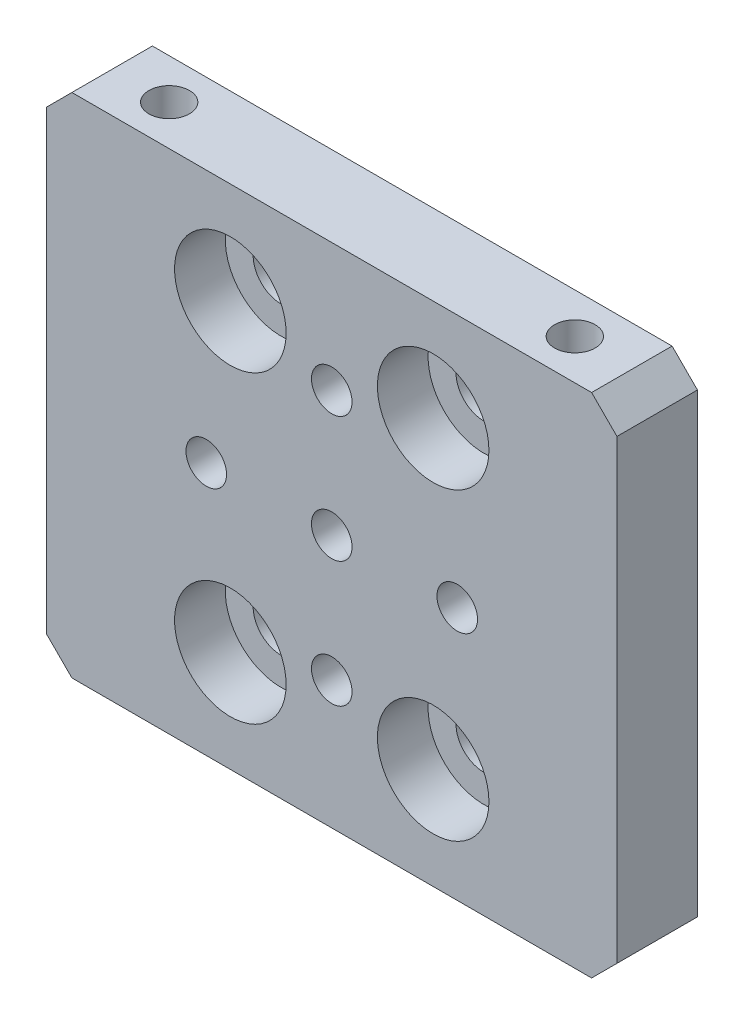
SolidWorks part; units mm, degrees
ref_plane "Front Plane" through (0, 0, 0) normal (0, 0, 1) x (1, 0, 0)
ref_plane "Top Plane" through (0, 0, 0) normal (0, 1, 0) x (1, 0, 0)
ref_plane "Right Plane" through (0, 0, 0) normal (1, 0, 0) x (0, 0, -1)
sketch "Sketch1" plane through (0, 0, 0) normal (0, 0, 1) x (1, 0, 0)
  line L1 (-11.25, 10) -> (11.25, 10)
  line L2 (-11.25, 10) -> (-11.25, -10)
  line L3 (-11.25, -10) -> (11.25, -10)
  line L4 (11.25, 10) -> (11.25, -10)
  line L5 (0, -10) -> (0, 10) construction
  line L6 (-11.25, 0) -> (11.25, 0) construction
  point P0 (0, 0)
  dimension "D1" = 20
  dimension "D2" = 22.5
extrude "Boss-Extrude1" add sketch "Sketch1" along normal blind 3.175
hole_wizard "CBORE for M2 SHCS1" positions "Sketch2" profile "Sketch3" counterbore size "M2" standard "ANSI Metric" end condition through all
sketch "Sketch2" plane through (0, 0, 3.175) normal (0, 0, 1) x (1, 0, 0)
  line L1 (-4, -6) -> (4, -6)
  line L2 (-4, -6) -> (-4, 6)
  line L3 (-4, 6) -> (4, 6)
  line L4 (4, -6) -> (4, 6)
  line L5 (0, 6) -> (0, -6) construction
  line L6 (-4, 0) -> (4, 0) construction
  point P2 (4, 6)
  point P909 (-4, -6)
  point P910 (-4, 6)
  point P924 (4, -6)
  dimension "D1" = 8
  dimension "D2" = 12
sketch "Sketch3" plane through (4, 6, 3.175) normal (1, 0, 0) x (0, -1, 0)
  line L0 (0, 0) -> (0, 3.175)
  line L1 (0, 3.175) -> (1.1, 3.175)
  line L3 (1.1, 3.175) -> (1.1, 2)
  line L4 (1.1, 2) -> (2.2, 2)
  line L5 (2.2, 2) -> (2.2, 0)
  line L7 (2.2, 0) -> (0, 0)
  line L11 (0, -6.35) -> (0, 107.95) construction
  dimension "Thru Hole Dia." = 2.2
  dimension "Thru Hole Depth" = 3.175
  dimension "C'Bore Dia." = 4.4
  dimension "C'Bore Depth" = 2
hole_wizard "Tap Drill for M2x0.4 Tap1" positions "Sketch5" profile "Sketch6" hole size "M2x0.4" standard "ANSI Metric" end condition through all
sketch "Sketch5" plane through (0, 10, 0) normal (0, 1, 0) x (1, 0, 0)
  line L0 (0, 0) -> (0, -3.175) construction
  line L1 (11.25, -3.175) -> (-11.25, -3.175) construction
  line L3 (0, -1.5875) -> (-8, -1.5875) construction
  point P9 (-8, -1.5875)
  point P16 (8, -1.5875)
  dimension "D1" = 8
sketch "Sketch6" plane through (8, 10, 1.5875) normal (1, 0, 0) x (0, 0, 1)
  line L0 (0, 0) -> (0, 20)
  line L1 (0, 20) -> (0.8, 20)
  line L2 (0.8, 20) -> (0.8, 0)
  line L5 (0.8, 0) -> (0, 0)
  line L11 (0, -6.35) -> (0, 107.95) construction
  dimension "Thru Hole Dia." = 1.6
  dimension "Thru Hole Depth" = 20
hole_wizard "Tap Drill for M2x0.4 Tap2" positions "Sketch7" profile "Sketch8" hole size "M2x0.4" standard "ANSI Metric" end condition through all
sketch "Sketch7" plane through (0, 0, 3.175) normal (0, 0, 1) x (1, 0, 0)
  line L2 (-4.9497, 0) -> (0, -4.9497)
  line L3 (-4.9497, 0) -> (0, 4.9497)
  line L4 (0, -4.9497) -> (4.9497, 0)
  line L5 (0, 4.9497) -> (4.9497, 0)
  line L6 (2.4749, -2.4749) -> (-2.4749, 2.4749) construction
  line L7 (-2.4749, -2.4749) -> (2.4749, 2.4749) construction
  line L8 (11.25, 10) -> (-11.25, 10) construction
  point P810 (0, 0)
  point P1137 (-4.9497, 0)
  point P1138 (0, -4.9497)
  point P1139 (4.9497, 0)
  point P1140 (0, 4.9497)
  dimension "D1" = 7
  dimension "D2" = 45
sketch "Sketch8" plane through (0, 0, 3.175) normal (1, 0, 0) x (0, -1, 0)
  line L0 (0, 0) -> (0, 3.175)
  line L1 (0, 3.175) -> (0.8, 3.175)
  line L2 (0.8, 3.175) -> (0.8, 0)
  line L5 (0.8, 0) -> (0, 0)
  line L11 (0, -6.35) -> (0, 107.95) construction
  dimension "Thru Hole Dia." = 1.6
  dimension "Thru Hole Depth" = 3.175
fillet "Fillet1" radius 1 4 edges at (-11.25, 10, 1.5875) (-11.25, -10, 1.5875) (11.25, -10, 1.5875) (11.25, 10, 1.5875) profile chamfer
